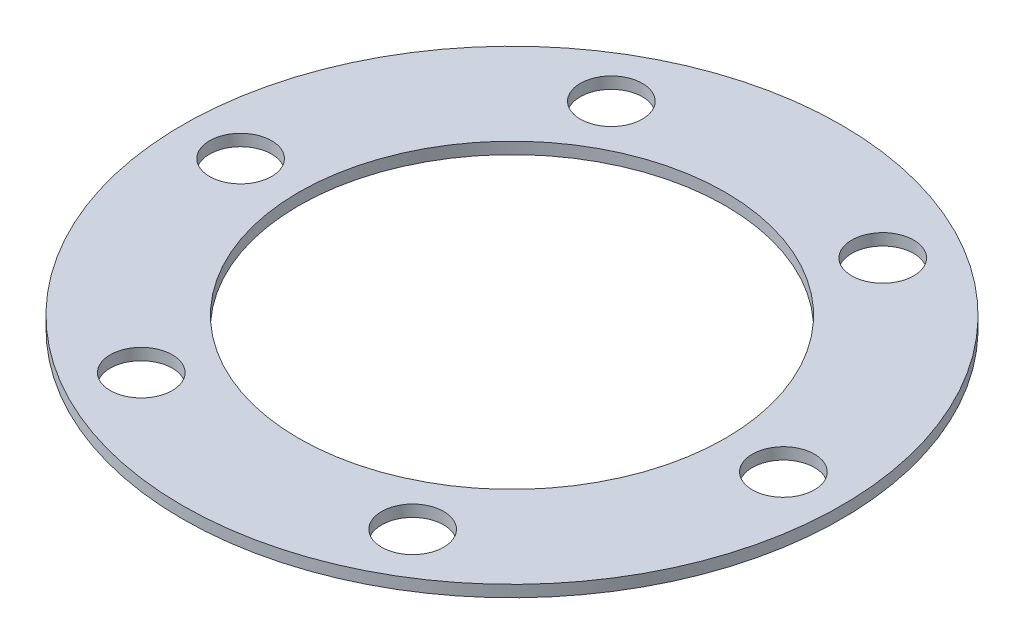
SolidWorks part; units mm, degrees
ref_plane "Front Plane" through (0, 0, 0) normal (0, 0, 1) x (1, 0, 0)
ref_plane "Top Plane" through (0, 0, 0) normal (0, 1, 0) x (1, 0, 0)
ref_plane "Right Plane" through (0, 0, 0) normal (1, 0, 0) x (0, 0, -1)
sketch "Sketch1" plane through (0, 0, 0) normal (0, 1, 0) x (1, 0, 0)
  circle A0 centre (0, 0) radius 55
  circle A1 centre (0, 0) radius 85
  dimension "D1" = 110
  dimension "D2" = 170
extrude "Boss-Extrude1" add sketch "Sketch1" along normal mid plane 3
sketch "Sketch2" plane through (0, 1.5, 0) normal (0, 1, 0) x (1, 0, 0)
  circle A0 centre (0, 0) radius 70 construction
  circle A1 centre (70, 0) radius 8
  circle A2 centre (35, -60.6218) radius 8
  circle A3 centre (-35, -60.6218) radius 8
  circle A4 centre (-70, 0) radius 8
  circle A5 centre (-35, 60.6218) radius 8
  circle A6 centre (35, 60.6218) radius 8
  point P5 (38.1519, 65.9636)
  point P6 (0, 0)
  point P18 (0, 0)
  dimension "D1" = 140
  dimension "D2" = 16
  dimension "D3" = 6
extrude "Cut-Extrude1" cut sketch "Sketch2" against normal through all both
